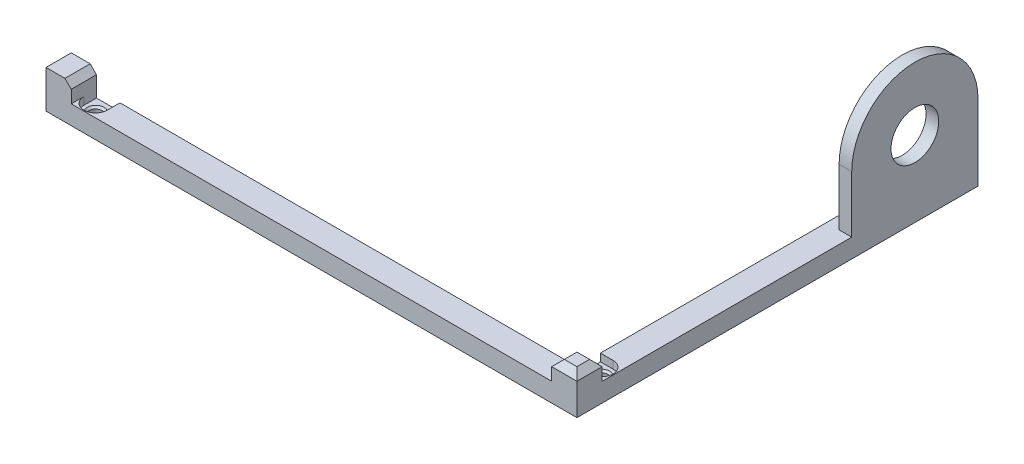
SolidWorks part; units mm, degrees
ref_plane "Front Plane" through (0, 0, 0) normal (0, 0, 1) x (1, 0, 0)
ref_plane "Top Plane" through (0, 0, 0) normal (0, 1, 0) x (1, 0, 0)
ref_plane "Right Plane" through (0, 0, 0) normal (1, 0, 0) x (0, 0, -1)
sketch "Sketch2" plane through (0, 0, 0) normal (0, 1, 0) x (1, 0, 0)
  line L0 (93.2338, 63) -> (93.2338, -71.4667)
  line L1 (93.2338, -71.4667) -> (-84.7672, -71.4667)
  line L2 (-84.7672, -71.4667) -> (-84.7672, -63)
  line L3 (-84.7672, -63) -> (84.7672, -63)
  line L4 (84.7672, -63) -> (84.7672, 63)
  line L5 (84.7672, 63) -> (93.2338, 63)
  point P2 (0, -63)
  point P7 (84.7672, 0)
  dimension "D1" = 8.4667
  dimension "D2" = 178.001
  dimension "D3" = 134.4667
extrude "Boss-Extrude1" add sketch "Sketch2" along normal blind 6.35
sketch "Sketch3" plane through (0, 6.35, 0) normal (0, 1, 0) x (1, 0, 0)
  line L0 (-84.7672, -71.4667) -> (93.2338, -71.4667) construction
  line L1 (-84.7672, -63) -> (-76.3005, -63)
  line L2 (-84.7672, -63) -> (-84.7672, -71.4667)
  line L3 (-84.7672, -71.4667) -> (-76.3005, -71.4667)
  line L4 (-76.3005, -63) -> (-76.3005, -71.4667)
  line L10 (93.2338, -71.4667) -> (93.2338, 63) construction
  line L11 (84.7672, -63) -> (93.2338, -63)
  line L12 (84.7672, -63) -> (84.7672, -71.4667)
  line L13 (84.7672, -71.4667) -> (93.2338, -71.4667)
  line L14 (93.2338, -63) -> (93.2338, -71.4667)
  line L15 (84.7672, 63) -> (84.7672, -63) construction
extrude "Boss-Extrude2" add sketch "Sketch3" along normal blind 6.35
sketch "Sketch8" plane through (0, 6.35, 0) normal (0, 1, 0) x (1, 0, 0)
  line L0 (84.7672, 63) -> (84.7672, -63) construction
  line L1 (93.2338, 63) -> (84.7672, 63)
  line L2 (93.2338, 63) -> (93.2338, 54.5333)
  line L3 (93.2338, 54.5333) -> (84.7672, 54.5333)
  line L4 (84.7672, 63) -> (84.7672, 54.5333)
extrude "Boss-Extrude4" add sketch "Sketch8" along normal blind 19.05
sketch "Sketch4" plane through (-84.7672, 0, 0) normal (-1, 0, 0) x (0, 0, 1)
  line L0 (64.0583, 8.4667) -> (67.2333, 11.6417)
  line L1 (64.0583, 8.4667) -> (67.2333, 5.2917)
  line L2 (67.2333, 11.6417) -> (70.4083, 8.4667)
  line L3 (67.2333, 5.2917) -> (70.4083, 8.4667)
  line L4 (64.0583, 8.4667) -> (70.4083, 8.4667) construction
  line L5 (67.2333, 11.6417) -> (67.2333, 5.2917) construction
  line L6 (63, 0) -> (71.4667, 0) construction
  line L7 (71.4667, 12.7) -> (71.4667, 0) construction
  point P1 (67.2333, 8.4667)
  dimension "D1" = 8.4667
  dimension "D2" = 6.35
  dimension "D3" = 4.2333
extrude "Cut-Extrude1" cut sketch "Sketch4" against normal blind 5.08
sketch "Sketch5" plane through (0, 0, -63) normal (0, 0, -1) x (-1, 0, 0)
  line L0 (-92.1755, 8.4667) -> (-89.0005, 11.6417)
  line L1 (-92.1755, 8.4667) -> (-89.0005, 5.2917)
  line L2 (-89.0005, 11.6417) -> (-85.8255, 8.4667)
  line L3 (-89.0005, 5.2917) -> (-85.8255, 8.4667)
  line L4 (-92.1755, 8.4667) -> (-85.8255, 8.4667) construction
  line L5 (-89.0005, 11.6417) -> (-89.0005, 5.2917) construction
  line L6 (-93.2338, 0) -> (-84.7672, 0) construction
  line L7 (-84.7672, 25.4) -> (-84.7672, 0) construction
  line L8 (-92.1755, 21.1667) -> (-89.0005, 24.3417)
  line L9 (-92.1755, 21.1667) -> (-89.0005, 17.9917)
  line L10 (-89.0005, 24.3417) -> (-85.8255, 21.1667)
  line L11 (-89.0005, 17.9917) -> (-85.8255, 21.1667)
  line L12 (-92.1755, 21.1667) -> (-85.8255, 21.1667) construction
  line L13 (-89.0005, 24.3417) -> (-89.0005, 17.9917) construction
  line L14 (-93.2338, 25.4) -> (-84.7672, 25.4) construction
  point P1 (-89.0005, 8.4667)
  point P10 (-89.0005, 21.1667)
  dimension "D1" = 8.4667
  dimension "D2" = 4.2333
  dimension "D3" = 6.35
  dimension "D4" = 4.2333
extrude "Cut-Extrude2" cut sketch "Sketch5" against normal blind 5.08
sketch "Sketch6" plane through (0, 0, 0) normal (0, -1, 0) x (1, 0, 0)
  line L0 (85.8255, 67.2333) -> (89.0005, 70.4083)
  line L1 (85.8255, 67.2333) -> (89.0005, 64.0583)
  line L2 (89.0005, 70.4083) -> (92.1755, 67.2333)
  line L3 (89.0005, 64.0583) -> (92.1755, 67.2333)
  line L4 (85.8255, 67.2333) -> (92.1755, 67.2333) construction
  line L5 (89.0005, 70.4083) -> (89.0005, 64.0583) construction
  line L12 (-84.7672, 71.4667) -> (93.2338, 71.4667) construction
  line L13 (93.2338, 71.4667) -> (93.2338, -63) construction
  point P1 (89.0005, 67.2333)
  dimension "D1" = 6.35
  dimension "D2" = 4.2333
  dimension "D3" = 4.2333
extrude "Cut-Extrude3" cut sketch "Sketch6" against normal blind 5.08
chamfer "Chamfer1" distance 0.635 angle 45 32 edges at (-79.6872, 10.0542, 65.6458) (-79.6872, 10.0542, 68.8208) (-79.6872, 6.8792, 68.8208) (-79.6872, 6.8792, 65.6458) (90.588, 10.0542, -57.92) (87.413, 10.0542, -57.92) (87.413, 6.8792, -57.92) (90.588, 6.8792, -57.92) (-84.7672, 6.8792, 68.8208) (-84.7672, 10.0542, 68.8208) (-84.7672, 6.8792, 65.6458) (-84.7672, 10.0542, 65.6458) (90.588, 6.8792, -63) (87.413, 6.8792, -63) (87.413, 10.0542, -63) (90.588, 10.0542, -63) (87.413, 5.08, 68.8208) (90.588, 5.08, 68.8208) (90.588, 5.08, 65.6458) (87.413, 5.08, 65.6458) (90.588, 0, 65.6458) (87.413, 0, 65.6458) (87.413, 0, 68.8208) (90.588, 0, 68.8208) (90.588, 22.7542, -57.92) (87.413, 22.7542, -57.92) (87.413, 19.5792, -57.92) (90.588, 19.5792, -57.92) (90.588, 19.5792, -63) (87.413, 19.5792, -63) (87.413, 22.7542, -63) (90.588, 22.7542, -63)
sketch "Sketch7" plane through (93.2338, 0, 0) normal (1, 0, 0) x (0, 0, -1)
  line L1 (-63, 6.35) -> (54.5333, 6.35) construction
  line L4 (20.6667, 25.4) -> (20.6667, 6.35)
  line L6 (20.6667, 6.35) -> (54.5333, 6.35)
  line L11 (63, 25.4) -> (63, 0) construction
  line L12 (54.5333, 25.4) -> (54.5333, 6.35) construction
  line L13 (63, 25.4) -> (54.5333, 25.4)
  line L14 (54.5333, 25.4) -> (54.5333, 6.35)
  circle A0 centre (41.8333, 25.4) radius 8
  arc A2 (63, 25.4) -> (20.6667, 25.4) centre (41.8333, 25.4) ccw
  dimension "D1" = 16
  dimension "D2" = 12.7
extrude "Boss-Extrude3" add sketch "Sketch7" against normal blind 4.2333
chamfer "Chamfer2" distance 2.1167 angle 45 6 edges at (-76.3005, 12.7, 67.2333) (86.8838, 25.4, -54.5333) (89.0005, 12.7, 63) (93.2338, 12.7, 67.2333) (89.0005, 12.7, 71.4667) (84.7672, 12.7, 67.2333)
sketch "Sketch9" plane through (0, 6.35, 0) normal (0, 1, 0) x (1, 0, 0)
  line L1 (84.7672, -63) -> (-76.3005, -63) construction
  line L2 (-76.3005, -67.2333) -> (-76.3005, -63)
  line L3 (-76.3005, -63) -> (-68.4265, -63)
  line L4 (-68.4265, -63) -> (-68.4265, -67.2333)
  line L6 (84.7672, 54.5333) -> (84.7672, -63) construction
  line L7 (89.0005, -55.126) -> (84.7672, -55.126)
  line L8 (84.7672, -55.126) -> (84.7672, -63)
  line L9 (84.7672, -63) -> (89.0005, -63)
  line L12 (-76.3005, -63) -> (-76.3005, -71.4667) construction
  line L13 (84.7672, -63) -> (86.8838, -65.1167) construction
  arc A0 (-76.3005, -67.2333) -> (-68.4265, -67.2333) centre (-72.3635, -67.2333) ccw
  arc A1 (89.0005, -63) -> (89.0005, -55.126) centre (89.0005, -59.063) ccw
  point P1 (84.7672, -63)
  point P2 (-76.3005, -63)
  dimension "D1" = 3.937
  dimension "D3" = 4.2333
extrude "Cut-Extrude5" cut sketch "Sketch9" against normal blind 2.54
sketch "Sketch11" plane through (0, 3.81, 0) normal (0, 1, 0) x (1, 0, 0)
  arc A0 (89.0005, -63) -> (89.0005, -55.126) centre (89.0005, -59.063) ccw construction
  arc A1 (-76.3005, -67.2333) -> (-68.4265, -67.2333) centre (-72.3635, -67.2333) ccw construction
  point P0 (89.0005, -59.063)
  point P1 (-72.3635, -67.2333)
hole_wizard "#18 (0.1695) Diameter Hole1" positions "Sketch11" profile "Sketch12" hole size "#18" standard "ANSI Inch"
sketch "Sketch12" plane through (89.0005, 3.81, 59.063) normal (1, 0, 0) x (0, 0, 1)
  line L0 (0, 0) -> (0, 5.8654)
  line L1 (0, 5.8654) -> (2.1526, 4.572)
  line L2 (2.1526, 4.572) -> (2.1526, 0.635)
  line L3 (2.1526, 0.635) -> (2.7876, 0)
  line L5 (2.7876, 0) -> (0, 0)
  line L6 (-2.1526, 0.635) -> (-2.7876, 0) construction
  line L10 (0, 5.8654) -> (-2.1526, 4.572) construction
  line L11 (0, -6.35) -> (0, 107.95) construction
  dimension "Hole Dia." = 4.3053
  dimension "Hole Depth" = 4.572
  dimension "Near C'Sink Dia." = 5.5753
  dimension "Near C'Sink Angle" = 90
  dimension "Drill Angle" = 118
